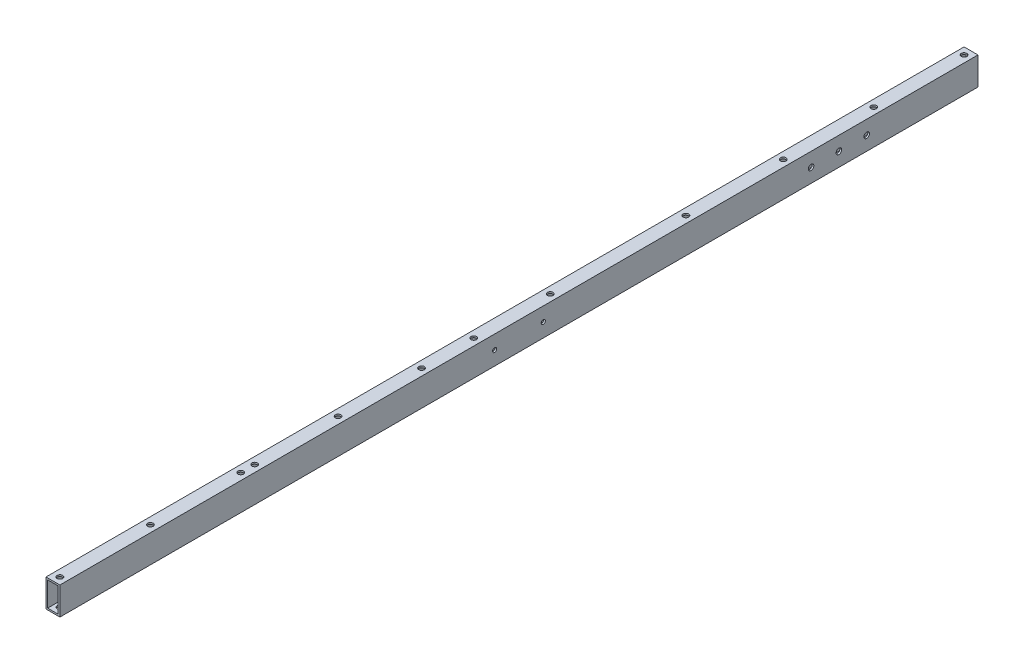
SolidWorks part; units mm, degrees
material "5052-H34"
ref_plane "正面" through (0, 0, 0) normal (0, 0, 1) x (1, 0, 0)
ref_plane "平面" through (0, 0, 0) normal (0, 1, 0) x (1, 0, 0)
ref_plane "右側面" through (0, 0, 0) normal (1, 0, 0) x (0, 0, -1)
sketch "ｽｹｯﾁ1" plane through (0, 0, 0) normal (0, 0, 1) x (1, 0, 0)
  line L1 (-5, 10) -> (5, 10)
  line L2 (-5, 10) -> (-5, -10)
  line L3 (-5, -10) -> (5, -10)
  line L4 (5, 10) -> (5, -10)
  line L5 (-5, 10) -> (5, -10) construction
  line L6 (-5, -10) -> (5, 10) construction
  point P0 (0, 0)
  dimension "D1" = 10
  dimension "D2" = 20
extrude "押し出し-薄板1" add sketch "ｽｹｯﾁ1" along normal blind 660 thin
sketch "ｽｹｯﾁ2" plane through (0, 10, 0) normal (0, 1, 0) x (1, 0, 0)
  line L0 (-5, -330) -> (5, -330) construction
  line L1 (-5, -660) -> (-5, 0) construction
  line L2 (5, -660) -> (5, 0) construction
  line L3 (0, -660) -> (0, -525) construction
  line L4 (5, -660) -> (-5, -660) construction
  line L5 (0, -525) -> (0, -515) construction
  line L6 (0, -302.5) -> (0, -357.5) construction
  line L7 (0, -515) -> (0, -395) construction
  circle A0 centre (0, -525) radius 2
  circle A1 centre (0, -655) radius 2
  circle A2 centre (0, -590) radius 2
  circle A3 centre (0, -5) radius 2
  circle A4 centre (0, -70) radius 2
  circle A5 centre (0, -135) radius 2
  circle A6 centre (0, -515) radius 2
  circle A8 centre (0, -357.5) radius 2
  circle A9 centre (0, -302.5) radius 2
  circle A10 centre (0, -395) radius 2
  circle A11 centre (0, -455) radius 2
  circle A12 centre (0, -205) radius 2
  point P26 (0, -330)
  dimension "D4" = 4
  dimension "D5" = 4
  dimension "D7" = 4
  dimension "D12" = 4
  dimension "D1" = 5
  dimension "D2" = 65
  dimension "D3" = 65
  dimension "D6" = 10
  dimension "D8" = 55
  dimension "D9" = 330
  dimension "D11" = 120
  dimension "D13" = 250
  dimension "D10" = 2
extrude "ｶｯﾄ - 押し出し1" cut sketch "ｽｹｯﾁ2" against normal through all
sketch "ｽｹｯﾁ3" plane through (5, 0, 0) normal (1, 0, 0) x (0, 0, -1)
  line L0 (-330, 10) -> (-330, -10) construction
  line L3 (-330, 0) -> (-312.5, 0) construction
  line L4 (0, -10) -> (0, 10) construction
  line L5 (-660, 10) -> (0, 10) construction
  line L6 (-100, 10) -> (-100, -10) construction
  line L7 (-660, -10) -> (0, -10) construction
  line L8 (-100, 0) -> (-80, 0) construction
  circle A0 centre (-312.5, 0) radius 1.5
  circle A1 centre (-347.5, 0) radius 1.5
  circle A2 centre (-100, 0) radius 2
  circle A3 centre (-80, 0) radius 2
  circle A4 centre (-120, 0) radius 2
  dimension "D1" = 3
  dimension "D5" = 4
  dimension "D2" = 35
  dimension "D3" = 330
  dimension "D4" = 100
  dimension "D6" = 40
extrude "ｶｯﾄ - 押し出し2" cut sketch "ｽｹｯﾁ3" against normal through all
